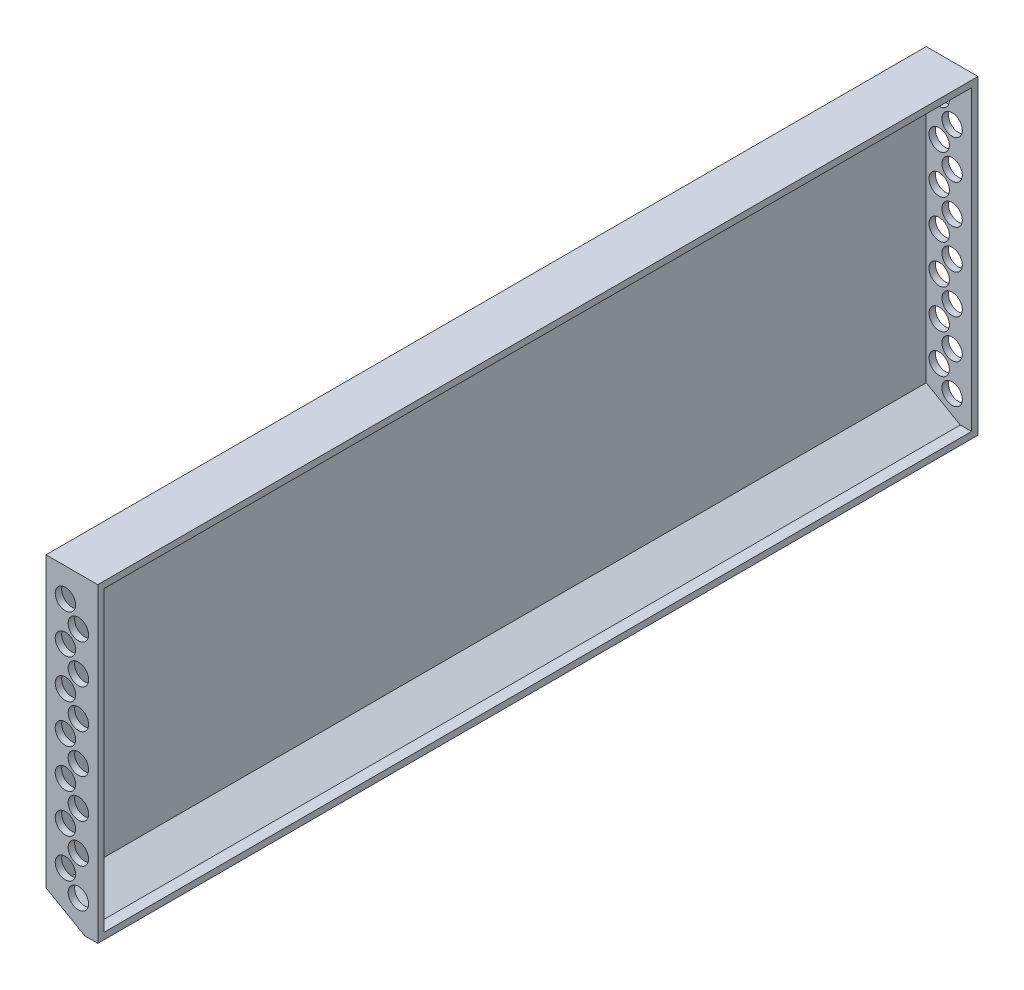
SolidWorks part; units mm, degrees
material "Custom Plastic"
ref_plane "X-Y Datum" through (0, 0, 0) normal (0, 0, 1) x (1, 0, 0)
ref_plane "X-Z Datum" through (0, 0, 0) normal (0, 1, 0) x (1, 0, 0)
ref_plane "Y-Z Datum" through (0, 0, 0) normal (1, 0, 0) x (0, 0, -1)
sketch "Sketch1" plane through (0, 0, 0) normal (0, 0, 1) x (1, 0, 0)
  line L0 (6.35, -76.2) -> (-12.7, -65.2878)
  line L1 (-12.7, 76.2) -> (12.7, 76.2)
  line L2 (-12.7, 76.2) -> (-12.7, -76.2)
  line L3 (-12.7, -76.2) -> (12.7, -76.2)
  line L4 (12.7, 76.2) -> (12.7, -76.2)
  line L5 (-12.7, 76.2) -> (12.7, -76.2) construction
  line L6 (-12.7, -76.2) -> (12.7, 76.2) construction
  point P0 (0, 0)
  dimension "D1" = 25.4
  dimension "D2" = 152.4
  dimension "D3" = 19.05
extrude "Boss-Extrude1" add sketch "Sketch1" along normal mid plane 431.8 contours L4 L1 L2 L0 L3
shell "Shell1" thickness 3.175
sketch "Sketch2" plane through (0, 0, 215.9) normal (0, 0, 1) x (1, 0, 0)
  line L0 (3.175, 76.2) -> (3.175, -74.3813) construction
  line L1 (-12.7, 76.2) -> (12.7, 76.2) construction
  line L2 (6.35, -76.2) -> (-12.7, -65.2878) construction
  line L3 (-3.175, -70.7439) -> (-3.175, 76.2) construction
  line L4 (12.7, 76.2) -> (12.7, -76.2) construction
  line L5 (-12.7, 76.2) -> (-12.7, -65.2878) construction
  circle A0 centre (3.175, -61.6813) radius 5
  circle A1 centre (-3.175, -52.1563) radius 5
  dimension "D1" = 10
  dimension "D2" = 9.525
  dimension "D3" = 9.525
  dimension "D4" = 9.525
  dimension "D5" = 12.7
extrude "Cut-Extrude1" cut sketch "Sketch2" against normal through all
pattern_linear "LPattern1" count 7 spacing 19.05 along (0, 1, 0) of "Cut-Extrude1"
